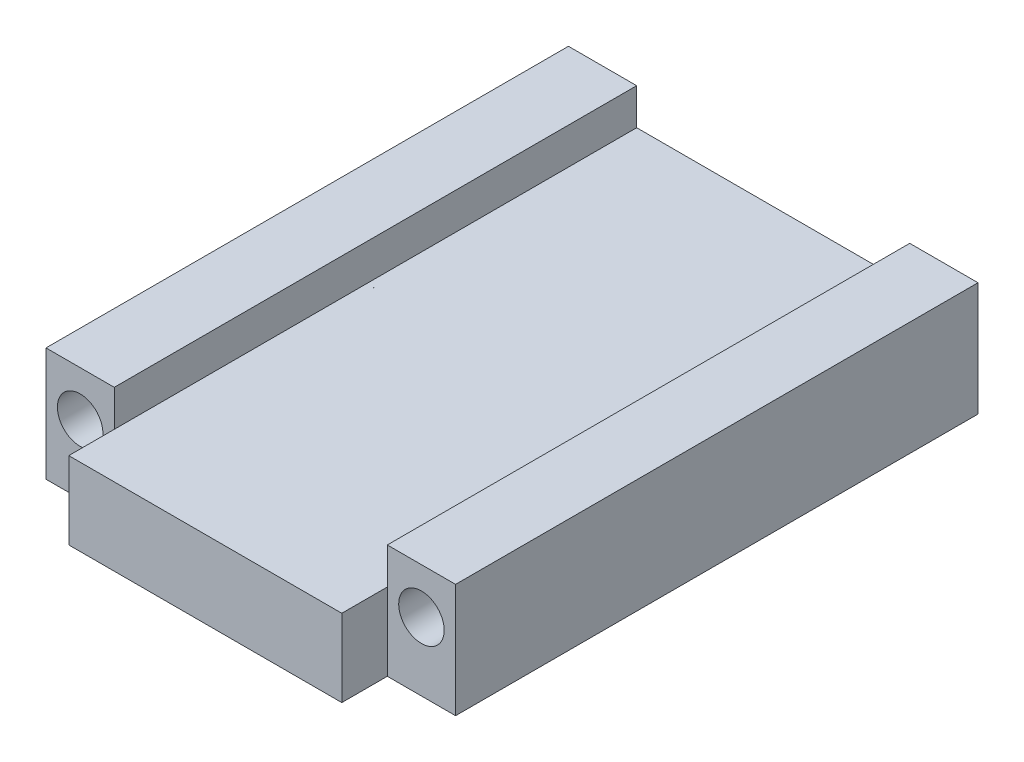
SolidWorks part; units mm, degrees
material "6063-O"
ref_plane "Front" through (0, 0, 0) normal (0, 0, 1) x (1, 0, 0)
ref_plane "Top" through (0, 0, 0) normal (0, 1, 0) x (1, 0, 0)
ref_plane "Right" through (0, 0, 0) normal (1, 0, 0) x (0, 0, -1)
sketch "Sketch1" plane through (0, 0, 0) normal (0, 0, 1) x (1, 0, 0)
  line L1 (14.2875, -3.9687) -> (-14.2875, -3.9688)
  line L2 (14.2875, -3.9687) -> (14.2875, 3.9688)
  line L3 (14.2875, 3.9688) -> (-14.2875, 3.9687)
  line L4 (-14.2875, -3.9688) -> (-14.2875, 3.9687)
  line L5 (14.2875, -3.9687) -> (-14.2875, 3.9687) construction
  line L6 (14.2875, 3.9688) -> (-14.2875, -3.9688) construction
  point P0 (0, 0)
  dimension "D1" = 7.9375
  dimension "D2" = 28.575
extrude "Boss-Extrude1" add sketch "Sketch1" along normal blind 39.624
sketch "Sketch2" plane through (0, 0, 39.624) normal (0, 0, 1) x (1, 0, 0)
  line L0 (9.525, 3.9688) -> (9.525, 1.4288)
  line L1 (14.2875, 3.9688) -> (-14.2875, 3.9688) construction
  line L2 (9.525, 1.4288) -> (-9.525, 1.4288)
  line L3 (-9.525, 1.4288) -> (-9.525, 3.9688)
  line L4 (-9.525, 3.9688) -> (9.525, 3.9688)
  line L5 (0, 0) -> (0, 21.8907) construction
  point P9 (0, 3.9688)
  dimension "D1" = 19.05
  dimension "D2" = 2.54
extrude "Cut-Extrude1" cut sketch "Sketch2" against normal through all
sketch "Sketch3" plane through (0, 0, 0) normal (0, 0, -1) x (-1, 0, 0)
  line L0 (-14.2875, 0.7938) -> (14.2875, 0.7938) construction
  line L1 (-14.2875, -3.9687) -> (-14.2875, 3.9688) construction
  line L2 (14.2875, 3.9687) -> (14.2875, -3.9688) construction
  line L3 (-14.2875, 3.9688) -> (-9.525, 3.9688) construction
  circle A0 centre (-11.9062, 0.7938) radius 1.5875
  circle A1 centre (11.9063, 0.7938) radius 1.5875
  dimension "D3" = 3.175
  dimension "D1" = 3.175
  dimension "D2" = 2.3813
  dimension "D4" = 2.3813
hole_wizard "1/8 (0.125) Clearance Dowel Hole1" positions "Sketch4" profile "Sketch5" hole size "1/8" standard "ANSI Inch" end condition through all
sketch "Sketch4" plane through (0, 0, 0) normal (0, 0, -1) x (-1, 0, 0)
  point P0 (-11.9062, 0.7938)
  point P3 (11.9063, 0.7938)
sketch "Sketch5" plane through (11.9062, 0.7938, 0) normal (1, 0, 0) x (0, 1, 0)
  line L0 (0, 0) -> (0, 39.624)
  line L1 (0, 39.624) -> (1.5875, 39.624)
  line L2 (1.5875, 39.624) -> (1.5875, 0)
  line L5 (1.5875, 0) -> (0, 0)
  line L11 (0, -6.35) -> (0, 107.95) construction
  dimension "Thru Hole Dia." = 3.175
  dimension "Thru Hole Depth" = 39.624
sketch "Sketch6" plane through (0, 0, 39.624) normal (0, 0, 1) x (1, 0, 0)
  line L0 (-14.2875, -3.9688) -> (14.2875, -3.9688) construction
  line L1 (-14.2875, 3.9687) -> (-9.525, 3.9687)
  line L2 (-14.2875, 3.9687) -> (-14.2875, -3.9688)
  line L3 (-14.2875, -3.9688) -> (-9.525, -3.9688)
  line L4 (-9.525, 3.9687) -> (-9.525, -3.9688)
  line L6 (14.2875, 3.9688) -> (9.525, 3.9687)
  line L7 (14.2875, 3.9688) -> (14.2875, -3.9688)
  line L8 (14.2875, -3.9688) -> (9.525, -3.9688)
  line L9 (9.525, 3.9687) -> (9.525, -3.9688)
  dimension "D1" = 4.7625
extrude "Cut-Extrude2" cut sketch "Sketch6" against normal blind 3.175
